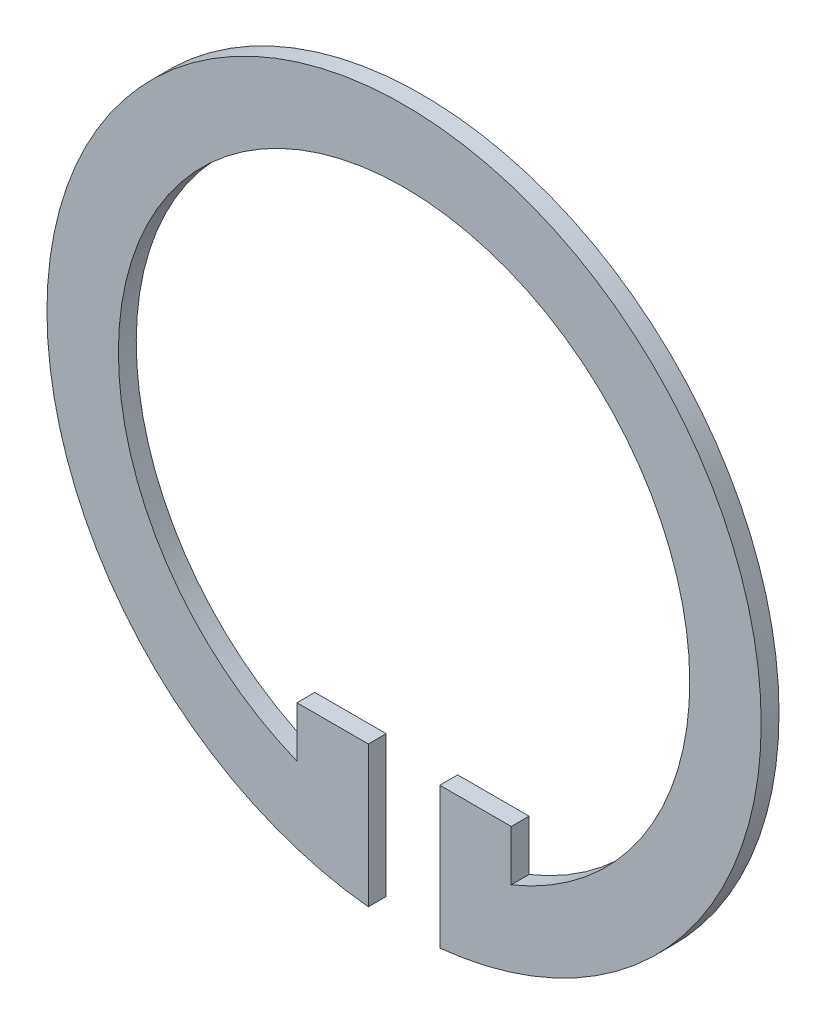
SolidWorks part; units mm, degrees
ref_plane "前视基准面" through (0, 0, 0) normal (0, 0, 1) x (1, 0, 0)
ref_plane "上视基准面" through (0, 0, 0) normal (0, 1, 0) x (1, 0, 0)
ref_plane "右视基准面" through (0, 0, 0) normal (1, 0, 0) x (0, 0, -1)
other "Configuration Table"
sketch "草图1" plane through (0, 0, 0) normal (0, 0, 1) x (1, 0, 0)
  line L0 (-3, -6) -> (-1, -6)
  line L1 (0, 0) -> (0, -13.5246) construction
  line L2 (-1, -6) -> (-1, -9.9499)
  line L3 (1, -6) -> (1, -9.9499)
  line L4 (1, -6) -> (3, -6)
  line L5 (-3, -6) -> (-3, -7.4162)
  line L6 (3, -6) -> (3, -7.4162)
  arc A0 (-1, -9.9499) -> (1, -9.9499) centre (0, 0) cw
  arc A1 (-3, -7.4162) -> (3, -7.4162) centre (0, 0) cw
  dimension "D4" = 10
  dimension "D5" = 8
  dimension "D1" = 6
  dimension "D2" = 2
  dimension "D3" = 2
extrude "凸台-拉伸1" add sketch "草图1" along normal blind 0.5
